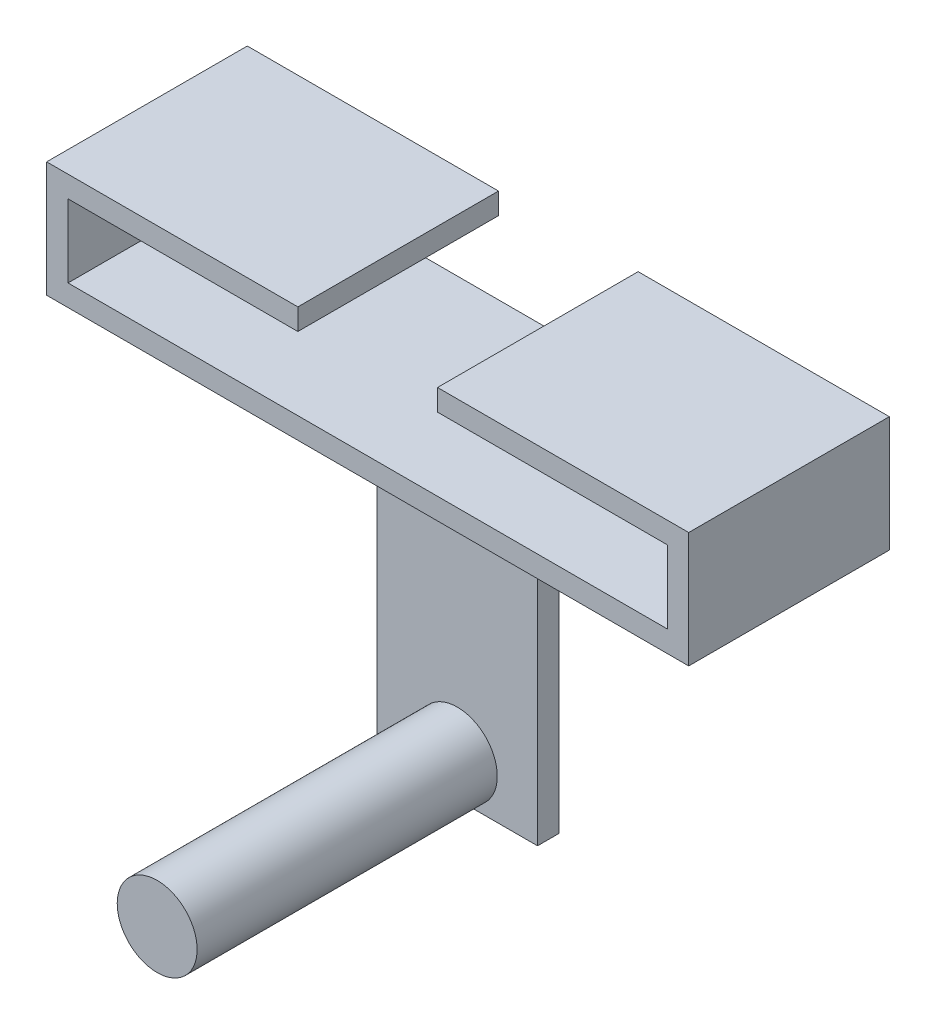
SolidWorks part; units mm, degrees
material "ASTM A36 Steel"
ref_plane "Front Plane" through (0, 0, 0) normal (0, 0, 1) x (1, 0, 0)
ref_plane "Top Plane" through (0, 0, 0) normal (0, 1, 0) x (1, 0, 0)
ref_plane "Right Plane" through (0, 0, 0) normal (1, 0, 0) x (0, 0, -1)
sketch "Sketch1" plane through (0, 0, 0) normal (0, 1, 0) x (1, 0, 0)
  line L1 (0, 0) -> (101.6, 0)
  line L2 (0, 0) -> (0, 31.75)
  line L3 (0, 31.75) -> (101.6, 31.75)
  line L4 (101.6, 0) -> (101.6, 31.75)
  dimension "D1" = 101.6
  dimension "D2" = 31.75
extrude "Boss-Extrude1" add sketch "Sketch1" along normal blind 18.288 contours L3 L4 L1 L2
sketch "Sketch2" plane through (0, 18.288, 0) normal (0, 1, 0) x (1, 0, 0)
  line L0 (0, 31.75) -> (101.6, 31.75) construction
  line L4 (39.751, 0) -> (39.751, 31.75)
  line L5 (0, 0) -> (101.6, 0) construction
  line L9 (61.849, 31.75) -> (61.849, 0)
  line L11 (39.751, 0) -> (61.849, 0)
  line L13 (39.751, 31.75) -> (61.849, 31.75)
  dimension "D1" = 22.098
  dimension "D2" = 39.751
extrude "Cut-Extrude1" cut sketch "Sketch2" against normal blind 14.9098
sketch "Sketch3" plane through (0, 0, 0) normal (0, 0, 1) x (1, 0, 0)
  line L0 (50.8, 3.3782) -> (50.8, 29.1234) construction
  line L1 (39.751, 3.3782) -> (3.3782, 3.3782)
  line L2 (39.751, 3.3782) -> (39.751, 14.9098)
  line L3 (39.751, 14.9098) -> (3.3782, 14.9098)
  line L4 (3.3782, 3.3782) -> (3.3782, 14.9098)
  line L5 (39.751, 3.3782) -> (61.849, 3.3782) construction
  line L6 (50.8, 29.1234) -> (50.8, -16.1656) construction
  line L7 (61.849, 14.9098) -> (98.2218, 14.9098)
  line L8 (98.2218, 3.3782) -> (98.2218, 14.9098)
  line L9 (61.849, 3.3782) -> (98.2218, 3.3782)
  line L10 (61.849, 3.3782) -> (61.849, 14.9098)
  dimension "D1" = 3.3782
  dimension "D2" = 3.3782
extrude "Cut-Extrude2" cut sketch "Sketch3" against normal through all
sketch "Sketch4" plane through (0, 0, 0) normal (0, -1, 0) x (1, 0, 0)
  line L0 (0, 0) -> (101.6, 0) construction
  line L1 (63.4898, -17.5641) -> (38.1102, -17.5641)
  line L2 (63.4898, -17.5641) -> (63.4898, -14.1859)
  line L3 (63.4898, -14.1859) -> (38.1102, -14.1859)
  line L4 (38.1102, -17.5641) -> (38.1102, -14.1859)
  line L5 (0, 0) -> (0, -31.75) construction
  point P4 (0, -15.875)
  point P5 (50.8, 0)
  point P6 (50.8, -14.1859)
  point P11 (38.1102, -15.875)
  dimension "D1" = 25.3797
extrude "Boss-Extrude2" add sketch "Sketch4" along normal blind 50.8
sketch "Sketch5" plane through (0, 0, -14.1859) normal (0, 0, 1) x (1, 0, 0)
  circle A0 centre (50.8, -44.45) radius 6.3246
  dimension "D1" = 12.6492
  dimension "D2" = 6.35
extrude "Boss-Extrude3" add sketch "Sketch5" along normal blind 47.498
equation "\"a\"= 1.006"
equation "\"b\"=0.9992"
equation "\"c\"= 0.133"
equation "\"d\"= 0.050"
equation "\"e\"=0.498"
equation "\"Overall Width\"= 4"
equation "\"width\"= 1.25"
equation "\"cylindrical diameter\"= 1.50"
equation "\"c beam length\"= 4'd"
equation "\"d beam length\"= 1"
equation "\"d beam width\"= 1.25"
equation "\"D1@Sketch1\"=\"Overall Width\""
equation "\"D2@Sketch1\"=\"width\""
equation "\"depth\"= 0.720"
equation "\"D1@Boss-Extrude1\"=\"depth\""
equation "\"cut length\"= 0.87"
equation "\"D1@Sketch2\"=\"cut length\""
equation "\"D1@Sketch4\"=\"b\""
equation "\"D2@Sketch4\"=\"c\""
equation "\"D1@Sketch5\"=\"e\""
